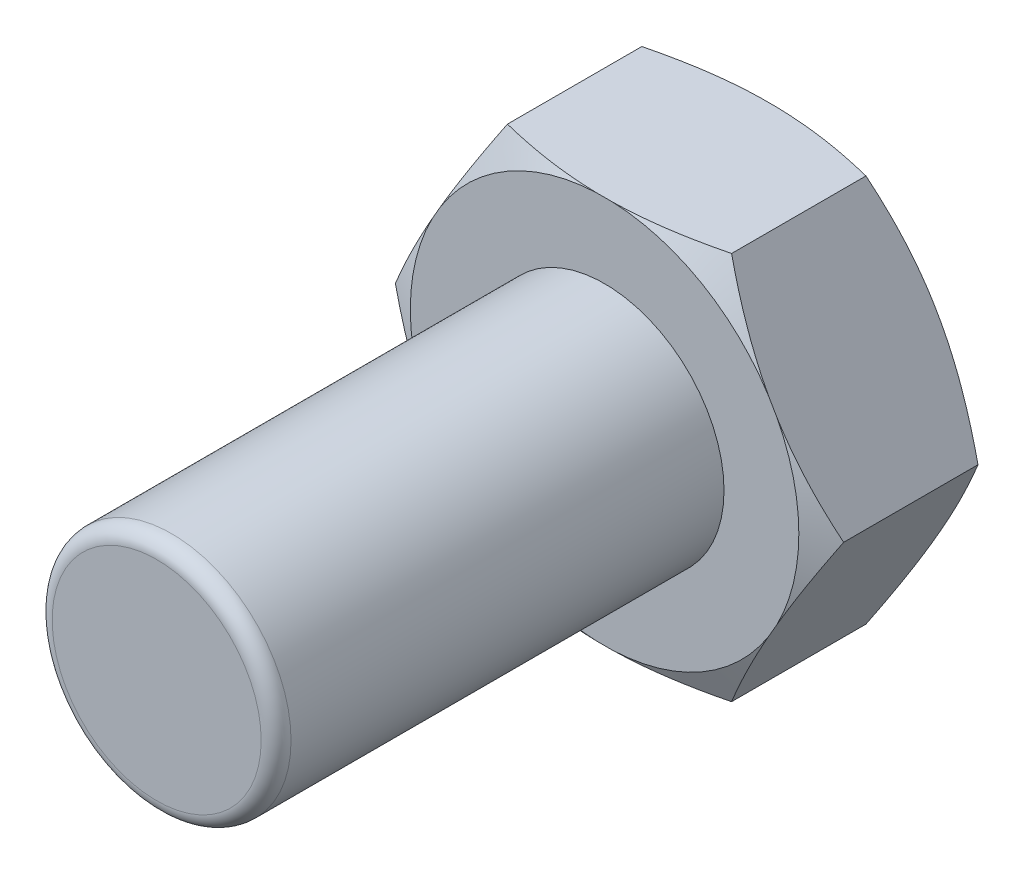
SolidWorks part; units mm, degrees
material "1.0036 (S235JRG1)"
ref_plane "Ön Düzlem" through (0, 0, 0) normal (0, 0, 1) x (1, 0, 0)
ref_plane "Üst Düzlem" through (0, 0, 0) normal (0, 1, 0) x (1, 0, 0)
ref_plane "Sağ Düzlem" through (0, 0, 0) normal (1, 0, 0) x (0, 0, -1)
sketch "Çizim1" plane through (0, 0, 0) normal (0, 0, 1) x (1, 0, 0)
  line L1 (7.5056, 0) -> (3.7528, 6.5)
  line L2 (3.7528, 6.5) -> (-3.7528, 6.5)
  line L3 (-3.7528, 6.5) -> (-7.5056, 0)
  line L4 (-7.5056, 0) -> (-3.7528, -6.5)
  line L5 (-3.7528, -6.5) -> (3.7528, -6.5)
  line L6 (3.7528, -6.5) -> (7.5056, 0)
  circle A0 centre (0, 0) radius 6.5 construction
  dimension "D1" = 13
extrude "Yükseklik-Ekstrüzyon1" add sketch "Çizim1" along normal blind 5.5
sketch "Çizim2" plane through (0, 0, 5.5) normal (0, 0, 1) x (1, 0, 0)
  circle A0 centre (0, 0) radius 4
  dimension "D1" = 8
extrude "Yükseklik-Ekstrüzyon2" add sketch "Çizim2" along normal blind 15
cosmetic thread "Kozmetik Diş Açma1" parameters "D2"=6.619
sketch "Çizim3" plane through (0, 0, 0) normal (0, 1, 0) x (1, 0, 0)
  line L0 (-7.5056, 0) -> (-6.5056, 0)
  line L1 (-3.7528, 0) -> (-7.5056, 0) construction
  line L2 (-6.5056, 0) -> (-7.5056, -0.5)
  line L3 (-7.5056, -5.5) -> (-7.5056, 0) construction
  line L4 (-7.5056, -0.5) -> (-7.5056, 0)
  line L9 (-7.5056, -5.5) -> (-7.5056, -5)
  line L10 (-7.5056, -5) -> (-6.5056, -5.5)
  line L11 (-3.7528, -5.5) -> (-7.5056, -5.5) construction
  line L12 (-6.5056, -5.5) -> (-7.5056, -5.5)
  line L13 (0, 0) -> (0, -5.5) construction
  line L14 (-4, -5.5) -> (4, -5.5) construction
  dimension "D1" = 1
  dimension "D2" = 0.5
  dimension "D3" = 0.5
  dimension "D4" = 1
revolve "Kes-Döndür1" cut sketch "Çizim3" angle 360 about L13
fillet "Radyus1" radius 0.5 1 edges at (4, 0, 20.5)
